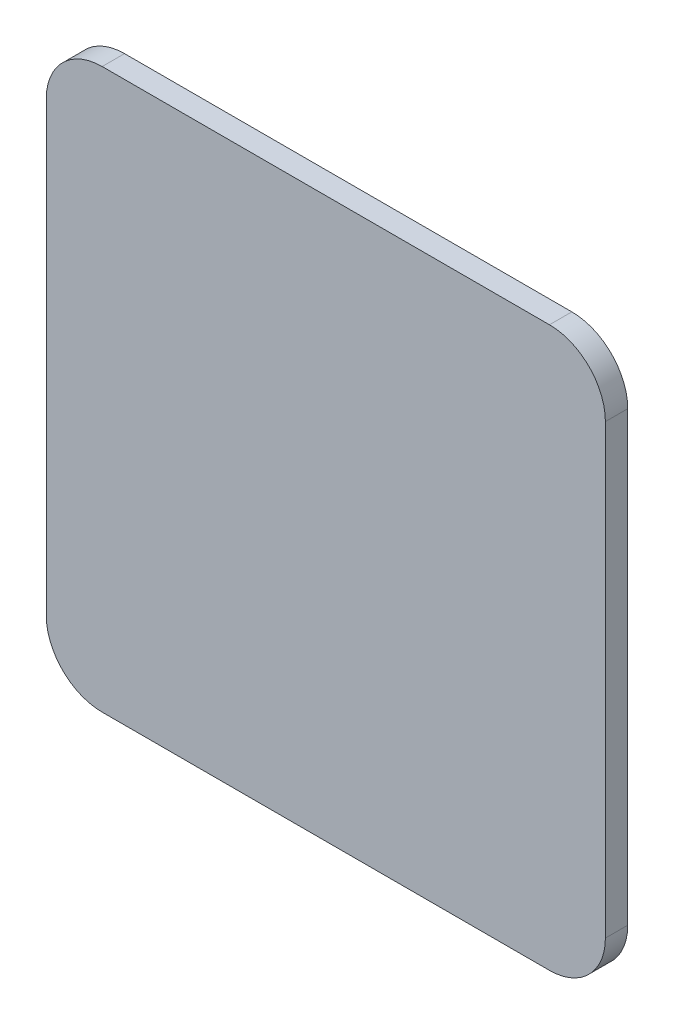
SolidWorks part; units mm, degrees
material "ABS"
ref_plane "Plan de face" through (0, 0, 0) normal (0, 0, 1) x (1, 0, 0)
ref_plane "Plan de dessus" through (0, 0, 0) normal (0, 1, 0) x (1, 0, 0)
ref_plane "Plan de droite" through (0, 0, 0) normal (1, 0, 0) x (0, 0, -1)
sketch "Esquisse1" plane through (0, 0, 0) normal (0, 0, 1) x (1, 0, 0)
  line L1 (0, 0) -> (10, 0)
  line L2 (0, 0) -> (0, 10)
  line L3 (0, 10) -> (10, 10)
  line L4 (10, 0) -> (10, 10)
  dimension "D1" = 10
extrude "Boss.-Extru.1" add sketch "Esquisse1" along normal blind 0.4
fillet "Congé1" radius 1 4 edges at (10, 0, 0.2) (0, 0, 0.2) (10, 10, 0.2) (0, 10, 0.2)
